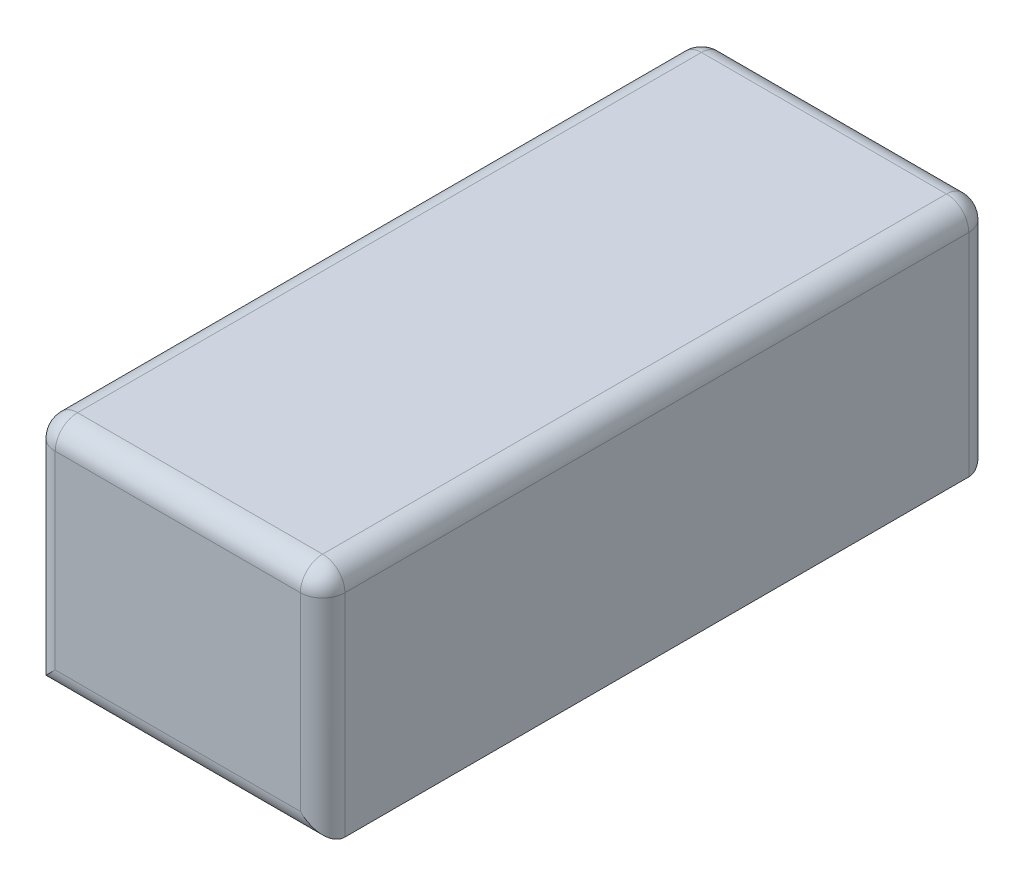
SolidWorks part; units mm, degrees
ref_plane "前视基准面" through (0, 0, 0) normal (0, 0, 1) x (1, 0, 0)
ref_plane "上视基准面" through (0, 0, 0) normal (0, 1, 0) x (1, 0, 0)
ref_plane "右视基准面" through (0, 0, 0) normal (1, 0, 0) x (0, 0, -1)
other "Configuration Table"
sketch "草图1" plane through (0, 0, 0) normal (0, 0, 1) x (1, 0, 0)
  line L1 (-13, 10.5) -> (13, 10.5)
  line L2 (-13, 10.5) -> (-13, -10.5)
  line L3 (-13, -10.5) -> (13, -10.5)
  line L4 (13, 10.5) -> (13, -10.5)
  line L5 (-13, 10.5) -> (13, -10.5) construction
  line L6 (-13, -10.5) -> (13, 10.5) construction
  point P0 (0, 0)
  dimension "D1" = 26
  dimension "D2" = 21
extrude "凸台-拉伸1" add sketch "草图1" along normal blind 60
fillet "圆角1" radius 2 10 edges at (-13, 0, 0) (0, -10.5, 0) (13, 0, 0) (0, -10.5, 60) (-13, 0, 60) (13, 0, 60) (13, 10.5, 30) (0, 10.5, 60) (-13, 10.5, 30) (0, 10.5, 0)
sketch "草图2" plane through (-13, 0, 0) normal (-1, 0, 0) x (0, 0, 1)
  line L4 (58, 8.5) -> (2, 8.5)
  line L5 (2, 8.5) -> (2, -10.5)
  line L6 (2, -10.5) -> (58, -10.5)
  line L7 (58, -10.5) -> (58, 8.5)
  line L8 (58, 8.5) -> (2, 8.5)
  line L9 (2, 8.5) -> (2, -10.5)
  line L10 (2, -10.5) -> (58, -10.5)
  line L11 (58, -10.5) -> (58, 8.5)
  circle A0 centre (37.7235, -5.5) radius 2.1 construction
  circle A1 centre (17.7235, 4.5) radius 2.1 construction
  circle A2 centre (-2.2765, -5.5) radius 2.1 construction
  circle A3 centre (37.7235, -5.5) radius 2.1
  circle A4 centre (17.7235, 4.5) radius 2.1
  circle A5 centre (-2.2765, -5.5) radius 2.1
  dimension "D1" = 0
